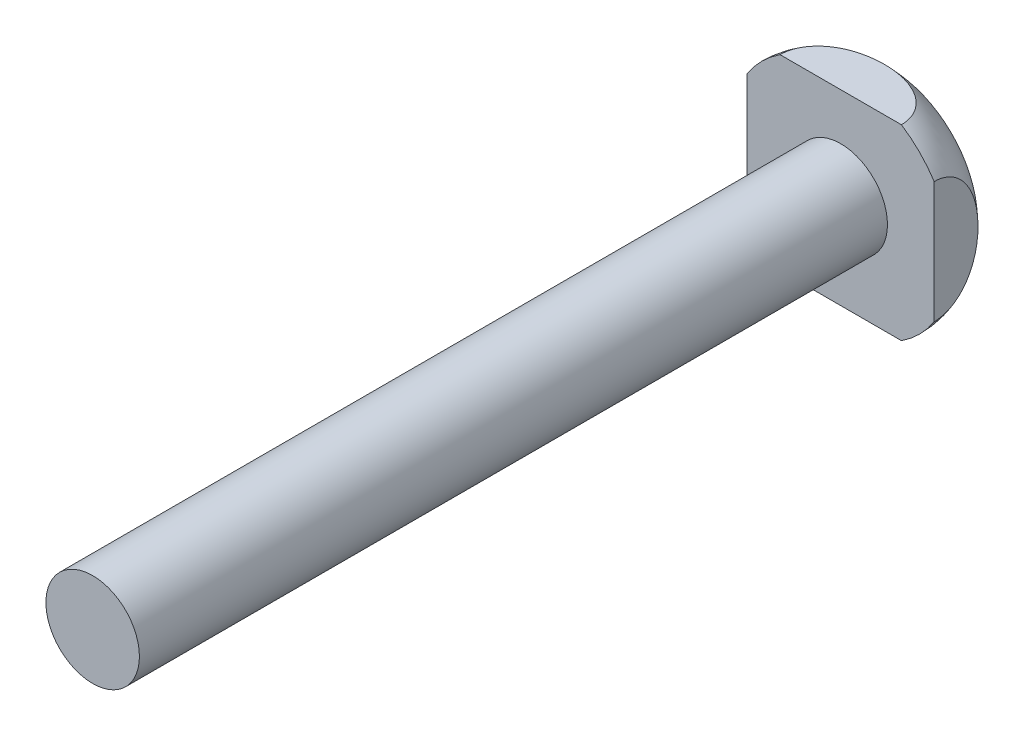
SolidWorks part; units mm, degrees
ref_plane "Front Plane" through (0, 0, 0) normal (0, 0, 1) x (1, 0, 0)
ref_plane "Top Plane" through (0, 0, 0) normal (0, 1, 0) x (1, 0, 0)
ref_plane "Right Plane" through (0, 0, 0) normal (1, 0, 0) x (0, 0, -1)
sketch "Sketch1" plane through (0, 0, 0) normal (0, 0, 1) x (1, 0, 0)
  line L1 (-12, -12) -> (12, -12)
  line L2 (-12, -12) -> (-12, 12)
  line L3 (-12, 12) -> (12, 12)
  line L4 (12, -12) -> (12, 12)
  line L5 (-12, -12) -> (12, 12) construction
  line L6 (-12, 12) -> (12, -12) construction
  point P0 (0, 0)
  dimension "D1" = 24
  dimension "D2" = 24
extrude "Boss-Extrude2" add sketch "Sketch1" along normal mid plane 8
sketch "Sketch3" plane through (0, 0, 4) normal (0, 0, 1) x (1, 0, 0)
  circle A0 centre (0, 0) radius 6
  dimension "D1" = 12
extrude "Boss-Extrude3" add sketch "Sketch3" along normal blind 96
sketch "Sketch5" plane through (0, 0, 0) normal (0, 1, 0) x (1, 0, 0)
  line L0 (0, 4) -> (0, 1.8406) construction
  line L1 (12, 4) -> (-12, 4) construction
  line L2 (0, 0.979) -> (0, 9.4321) construction
  line L3 (0, 4) -> (6.3063, 4)
  line L7 (6.3063, 4) -> (6.3063, -4) construction
  line L8 (14.3063, -4) -> (24.3063, -4)
  line L9 (0, 14) -> (0, 4)
  arc A2 (14.3063, -4) -> (6.3063, 4) centre (6.3063, -4) ccw
  arc A4 (0, 14) -> (24.3063, -4) centre (0, -11.411) cw
  point P5 (21.6638, -4)
  dimension "D1" = 8
  dimension "D2" = 10
  dimension "D3" = 10
revolve "Cut-Revolve8" cut sketch "Sketch5" angle 360 about L0
